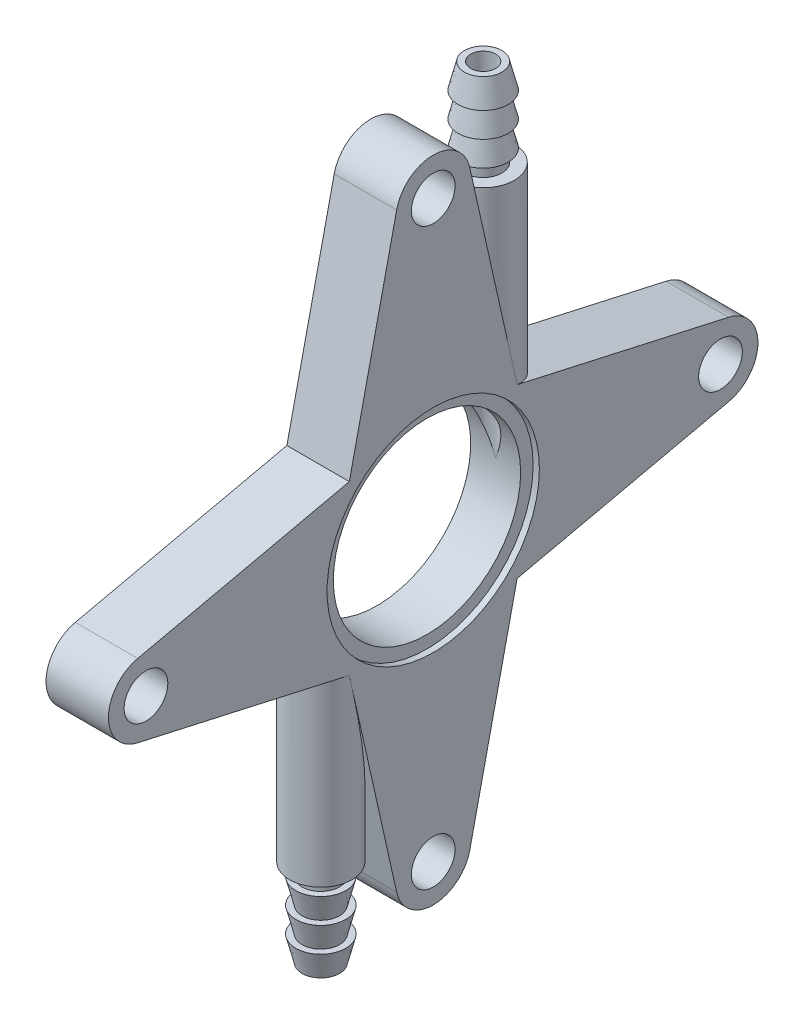
SolidWorks part; units mm, degrees
ref_plane "Front Plane" through (0, 0, 0) normal (0, 0, 1) x (1, 0, 0)
ref_plane "Top Plane" through (0, 0, 0) normal (0, 1, 0) x (1, 0, 0)
ref_plane "Right Plane" through (0, 0, 0) normal (1, 0, 0) x (0, 0, -1)
sketch "Sketch2" plane through (0, 0, 0) normal (1, 0, 0) x (0, 0, -1)
  line L0 (0, 0) -> (21.1543, 21.1543) construction
  line L1 (0, 0) -> (-22.0712, 22.0712) construction
  line L3 (-6.7175, 6.7175) -> (-2.9276, 23.6551)
  line L4 (6.7175, 6.7175) -> (2.9276, 23.6551)
  line L5 (-6.7175, -6.7175) -> (-23.6551, -2.9276)
  line L6 (-6.7175, 6.7175) -> (-23.6551, 2.9276)
  line L7 (6.7175, -6.7175) -> (2.9276, -23.6551)
  line L8 (-6.7175, -6.7175) -> (-2.9276, -23.6551)
  line L9 (6.7175, 6.7175) -> (23.6551, 2.9276)
  line L10 (6.7175, -6.7175) -> (23.6551, -2.9276)
  circle A1 centre (0, 23) radius 1.75
  circle A2 centre (23, 0) radius 1.75
  circle A3 centre (0, -23) radius 1.75
  circle A4 centre (-23, 0) radius 1.75
  circle A5 centre (0, 0) radius 7.5
  circle A6 centre (0, 0) radius 8.5 construction
  circle A8 centre (0, 0) radius 21.25 construction
  circle A10 centre (0, 0) radius 9.5 construction
  arc A11 (-2.9276, 23.6551) -> (2.9276, 23.6551) centre (0, 23) cw
  arc A12 (-23.6551, -2.9276) -> (-23.6551, 2.9276) centre (-23, 0) cw
  arc A13 (2.9276, -23.6551) -> (-2.9276, -23.6551) centre (0, -23) cw
  arc A14 (23.6551, 2.9276) -> (23.6551, -2.9276) centre (23, 0) cw
  point P14 (0, 0)
  point P41 (0, 0)
  point P49 (0, 0)
  dimension "D1" = 15
  dimension "D3" = 3.5
  dimension "D5" = 19
  dimension "D6" = 17
  dimension "D7" = 3
  dimension "D4" = 23
  dimension "D2" = 4
  dimension "D8" = 4
extrude "Flange" add sketch "Sketch2" along normal blind 5
sketch "Sketch3" plane through (5, 0, 0) normal (1, 0, 0) x (0, 0, -1)
  circle A0 centre (0, 0) radius 8.5
  dimension "D1" = 17
extrude "O-Ring Seat" cut sketch "Sketch3" against normal blind 0.5
ref_plane "MidPlane Reference" through (2.5, 0, 0) normal (1, 0, 0) x (0, 0, -1)
mirror "Mirror1" about plane through (2.5, 0, 0) normal (1, 0, 0) of "O-Ring Seat"
sketch "Sketch5" plane through (0, 0, 0) normal (0, 1, 0) x (1, 0, 0)
  line L0 (2.5, -29.7) -> (2.5, 29.7) construction
  circle A0 centre (2.5, 6.5) radius 1
  dimension "D1" = 2
  dimension "D2" = 6.5
extrude "Outlet" cut sketch "Sketch5" along normal through all
ref_plane "TopPlane" through (0, 26, 0) normal (0, 1, 0) x (1, 0, 0)
ref_plane "Plane1" through (0, 21, 0) normal (0, 1, 0) x (1, 0, 0)
sketch "Sketch6" plane through (0, 21, 0) normal (0, 1, 0) x (1, 0, 0)
  circle A2 centre (2.5, 6.5) radius 1
  circle A3 centre (2.5, 6.5) radius 2.5
  dimension "D1" = 5
extrude "Boss-Extrude2" add sketch "Sketch6" against normal up to next
sketch "Sketch8" plane through (2.5, 0, 0) normal (1, 0, 0) x (0, 0, -1)
  line L0 (5, 21) -> (5, 22)
  line L1 (5, 22) -> (4.5, 22)
  line L2 (4.5, 22) -> (5, 24)
  line L3 (5, 24) -> (4.5, 24)
  line L4 (4.5, 24) -> (5, 26)
  line L5 (5, 26) -> (4.5, 26)
  line L6 (4.5, 26) -> (5, 28)
  line L7 (5, 28) -> (5.5, 28)
  line L8 (5.5, 28) -> (5.5, 21)
  line L9 (5.5, 21) -> (5, 21)
  line L10 (9, 21) -> (4, 21) construction
  line L11 (7.5, 21) -> (5.5, 21) construction
  point P14 (6.5, 21)
  dimension "D1" = 1
  dimension "D2" = 0.5
  dimension "D3" = 0.5
  dimension "D4" = 2
  dimension "D5" = 1
ref_axis "Axis1" through (2.5, 26, -6.5) along (0, -1, 0)
revolve "Revolve1" add sketch "Sketch8" angle 360 about axis through (2.5, 26, -6.5) along (0, -1, 0)
pattern_circular "CirPattern1" count 2 every 180 about axis through (0.5, 0, 0) along (-1, 0, 0) of "Outlet", "Boss-Extrude2", "Revolve1"
